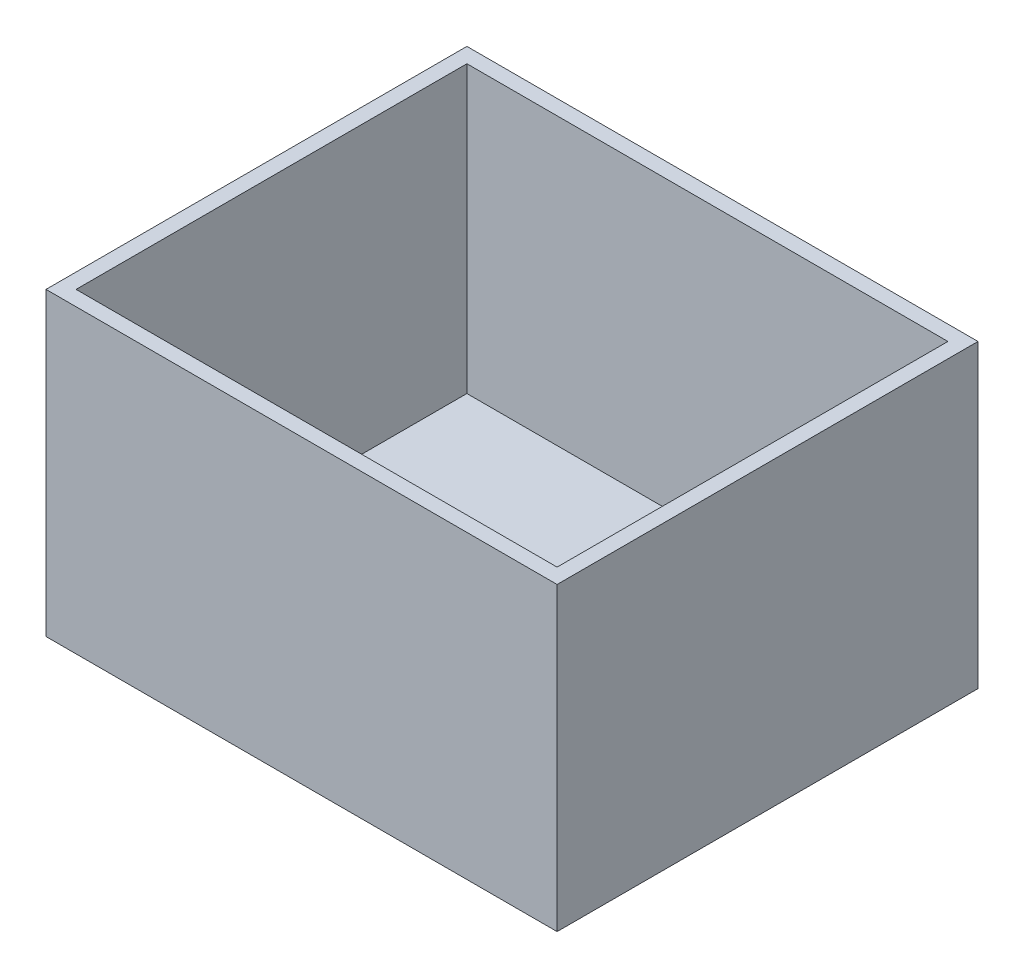
SolidWorks part; units mm, degrees
ref_plane "Front Plane" through (0, 0, 0) normal (0, 0, 1) x (1, 0, 0)
ref_plane "Top Plane" through (0, 0, 0) normal (0, 1, 0) x (1, 0, 0)
ref_plane "Right Plane" through (0, 0, 0) normal (1, 0, 0) x (0, 0, -1)
sketch "Sketch1" plane through (0, 0, 0) normal (0, 1, 0) x (1, 0, 0)
  line L1 (0, 0) -> (86.36, 0)
  line L2 (0, 0) -> (0, 71.12)
  line L3 (0, 71.12) -> (86.36, 71.12)
  line L4 (86.36, 0) -> (86.36, 71.12)
  dimension "D1" = 86.36
  dimension "D2" = 71.12
extrude "Boss-Extrude3" add sketch "Sketch1" along normal blind 50.8 contours L2 L3 L4 L1
sketch "Sketch3" plane through (0, 50.8, 0) normal (0, 1, 0) x (1, 0, 0)
  line L0 (0, 71.12) -> (86.36, 71.12) construction
  line L1 (2.54, 68.58) -> (83.82, 68.58)
  line L2 (2.54, 68.58) -> (2.54, 2.54)
  line L3 (2.54, 2.54) -> (83.82, 2.54)
  line L4 (83.82, 68.58) -> (83.82, 2.54)
  line L5 (0, 0) -> (0, 71.12) construction
  dimension "D1" = 81.28
  dimension "D2" = 66.04
  dimension "D3" = 2.54
  dimension "D4" = 2.54
extrude "Cut-Extrude1" cut sketch "Sketch3" against normal blind 48.26
sketch "Sketch4" plane through (0, 2.54, 0) normal (0, 1, 0) x (1, 0, 0)
  line L2 (83.82, 2.54) -> (83.82, 68.58) construction
  line L3 (2.54, 2.54) -> (83.82, 2.54) construction
  line L5 (2.54, 2.54) -> (83.82, 2.54) construction
  circle A0 centre (27.94, 36.576) radius 1.524
  circle A1 centre (63.5, 36.576) radius 1.524
  circle A2 centre (63.5, 6.35) radius 1.524
  circle A3 centre (27.94, 6.35) radius 1.524
  dimension "D1" = 35.56
  dimension "D2" = 30.226
  dimension "D3" = 20.32
  dimension "D4" = 30.226
  dimension "D5" = 20.32
  dimension "D6" = 3.81
  dimension "D7" = 35.56
  dimension "D8" = 3.81
extrude "Boss-Extrude7" add sketch "Sketch4" along normal blind 6.35
